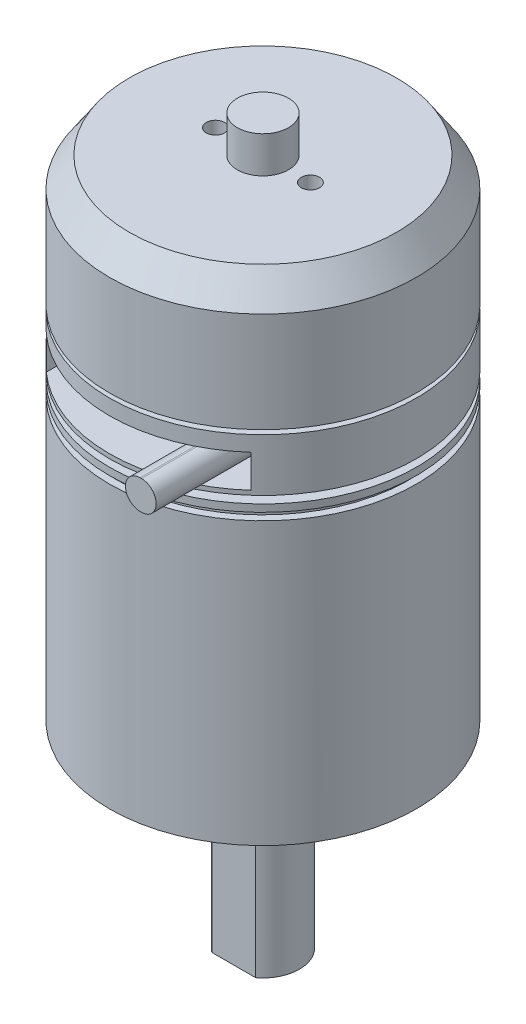
SolidWorks part; units mm, degrees
ref_plane "前视基准面" through (0, 0, 0) normal (0, 0, 1) x (1, 0, 0)
ref_plane "上视基准面" through (0, 0, 0) normal (0, 1, 0) x (1, 0, 0)
ref_plane "右视基准面" through (0, 0, 0) normal (1, 0, 0) x (0, 0, -1)
sketch "草图1" plane through (0, 0, 0) normal (0, 0, 1) x (1, 0, 0)
  line L0 (0, 0) -> (4.1, 0)
  line L1 (4.1, 0) -> (4.1, 6.7)
  line L2 (4.1, 6.7) -> (13.4, 6.7)
  line L3 (13.4, 6.7) -> (13.4, 8.7)
  line L4 (13.4, 8.7) -> (21, 8.7)
  line L5 (21, 8.7) -> (21, 10.2)
  line L6 (21, 10.2) -> (20, 10.2)
  line L7 (20, 10.2) -> (20, 11.2)
  line L8 (20, 11.2) -> (21, 11.2)
  line L9 (21, 11.2) -> (21, 12.2)
  line L10 (21, 12.2) -> (10, 12.2)
  line L11 (10, 12.2) -> (10, 13.2)
  line L12 (10, 13.2) -> (21, 13.2)
  line L13 (21, 13.2) -> (21, 20.4)
  line L14 (21, 20.4) -> (5, 20.4)
  line L15 (5, 20.4) -> (5, 21)
  line L16 (5, 21) -> (21, 21)
  line L17 (21, 21) -> (21, 34.7)
  line L18 (21, 34.7) -> (18.3, 38.7)
  line L19 (18.3, 38.7) -> (3.5, 38.7)
  line L20 (3.5, 38.7) -> (3.5, 43.7)
  line L21 (3.5, 43.7) -> (0, 43.7)
  line L22 (0, 43.7) -> (0, 0) construction
  line L23 (0, 0) -> (0, 43.7)
  dimension "D1" = 8.2
  dimension "D2" = 26.8
  dimension "D3" = 42
  dimension "D4" = 10
  dimension "D5" = 1.5
  dimension "D6" = 1
  dimension "D7" = 1
  dimension "D8" = 20
  dimension "D9" = 1
  dimension "D10" = 7.2
  dimension "D11" = 0.6
  dimension "D12" = 13.7
  dimension "D13" = 5
  dimension "D14" = 2
  dimension "D15" = 6.7
  dimension "D16" = 1
  dimension "D17" = 7
  dimension "D18" = 36.6
  dimension "D19" = 4
  dimension "D20" = 30
revolve "旋转1" add sketch "草图1" angle 360 about L22
ref_plane "基准面1" through (0, 0, 21) normal (0, 0, 1) x (1, 0, 0)
sketch "草图2" plane through (0, 0, 21) normal (0, 0, 1) x (1, 0, 0)
  line L1 (-14, 18.3) -> (14, 18.3)
  line L2 (-14, 18.3) -> (-14, 13.8)
  line L3 (-14, 13.8) -> (14, 13.8)
  line L4 (14, 18.3) -> (14, 13.8)
  line L5 (-14, 18.3) -> (14, 13.8) construction
  line L6 (-14, 13.8) -> (14, 18.3) construction
  line L7 (-21, 13.2) -> (21, 13.2) construction
  point P0 (0, 16.05)
  dimension "D1" = 28
  dimension "D2" = 4.5
  dimension "D3" = 0.6
extrude "切除-拉伸1" cut sketch "草图2" against normal blind 10
sketch "草图3" plane through (0, 0, 11) normal (0, 0, 1) x (1, 0, 0)
  line L0 (9.1851, 16.0532) -> (9.3851, 16.0532) construction
  line L1 (9.1851, 18.0532) -> (9.3851, 18.0532)
  line L2 (9.1851, 14.0532) -> (9.3851, 14.0532)
  arc A0 (9.1851, 18.0532) -> (9.1851, 14.0532) centre (9.1851, 16.0532) ccw
  arc A1 (9.3851, 14.0532) -> (9.3851, 18.0532) centre (9.3851, 16.0532) ccw
  point P2 (9.2851, 16.0532)
  dimension "D1" = 4
  dimension "D2" = 0.2
extrude "凸台-拉伸1" add sketch "草图3" along normal blind 15
hole_wizard "M3 螺纹孔1" positions "草图5" profile "草图6" tap size "M3" standard "GB"
sketch "草图5" plane through (0, 38.7, 0) normal (0, 1, 0) x (1, 0, 0)
  line L0 (0, 0) -> (0, 8.0606) construction
  point P0 (-6.5, 0)
  point P2 (6.5, 0)
  dimension "D1" = 13
sketch "草图6" plane through (-6.5, 38.7, 0) normal (1, 0, 0) x (0, 0, 1)
  line L0 (0, 0) -> (0, 4.7511)
  line L1 (0, 4.7511) -> (1.25, 4)
  line L2 (1.25, 4) -> (1.25, 0)
  line L5 (1.25, 0) -> (0, 0)
  line L10 (0, 4.7511) -> (-1.25, 4) construction
  line L11 (0, -6.35) -> (0, 107.95) construction
  dimension "螺纹孔钻头直径" = 2.5
  dimension "螺纹孔钻头深度" = 4
  dimension "导头角度" = 118
cosmetic thread "孔螺蚊线1" parameters "D1"=4, "D2"=3
cosmetic thread "孔螺蚊线2" parameters "D1"=4, "D2"=3
sketch "草图7" plane through (0, 0, 0) normal (0, 0, 1) x (1, 0, 0)
  line L0 (0, 8.7) -> (0, -55.3) construction
  line L1 (-13.4, 8.7) -> (13.4, 8.7) construction
  line L2 (0, -55.3) -> (5, -55.3)
  line L3 (5, -55.3) -> (5, -31.2)
  line L4 (5, -31.2) -> (8.275, -31.2)
  line L5 (13, -30.3) -> (13, -28.3)
  line L6 (13, -28.3) -> (21, -28.3)
  line L7 (21, -28.3) -> (21, 8.7)
  line L8 (-21, 8.7) -> (21, 8.7) construction
  line L9 (21, 8.7) -> (0, 8.7)
  line L10 (18.3, 38.7) -> (-18.3, 38.7) construction
  line L11 (13, -30.3) -> (8.275, -30.3)
  line L12 (8.275, -30.3) -> (8.275, -31.2)
  line L13 (0, 8.7) -> (0, -55.3)
  dimension "D1" = 67
  dimension "D2" = 2
  dimension "D3" = 0.9
  dimension "D4" = 27
  dimension "D5" = 26
  dimension "D6" = 10
  dimension "D7" = 16.55
revolve "旋转2" add sketch "草图7" angle 360 about L0
sketch "草图8" plane through (0, -55.3, 0) normal (0, -1, 0) x (1, 0, 0)
  line L0 (-3, 4) -> (3, 4)
  circle A0 centre (0, 0) radius 5 construction
  circle A1 centre (0, 0) radius 5 construction
  arc A2 (3, 4) -> (-3, 4) centre (0, 0) ccw
  dimension "D1" = 4
extrude "切除-拉伸2" cut sketch "草图8" against normal blind 20
hole_wizard "M4 螺纹孔1" positions "草图10" profile "草图9" tap size "M4" standard "GB"
sketch "草图10" plane through (0, -28.3, 0) normal (0, -1, 0) x (-1, 0, 0)
  circle A0 centre (0, 0) radius 17.5
  point P5 (0, -17.5)
  point P7 (-17.5, 0)
  point P9 (0, 17.5)
  point P11 (17.5, 0)
  dimension "D1" = 35
sketch "草图9" plane through (-17.5, -28.3, 0) normal (1, 0, 0) x (0, 0, -1)
  line L0 (0, 0) -> (0, 11.0914)
  line L1 (0, 11.0914) -> (1.65, 10.1)
  line L2 (1.65, 10.1) -> (1.65, 0)
  line L5 (1.65, 0) -> (0, 0)
  line L10 (0, 11.0914) -> (-1.65, 10.1) construction
  line L11 (0, -6.35) -> (0, 107.95) construction
  dimension "螺纹孔钻头直径" = 3.3
  dimension "螺纹孔钻头深度" = 10.1
  dimension "导头角度" = 118
cosmetic thread "孔螺蚊线3" parameters "D1"=8, "D2"=4
cosmetic thread "孔螺蚊线4" parameters "D1"=8, "D2"=4
cosmetic thread "孔螺蚊线5" parameters "D1"=8, "D2"=4
cosmetic thread "孔螺蚊线6" parameters "D1"=8, "D2"=4
